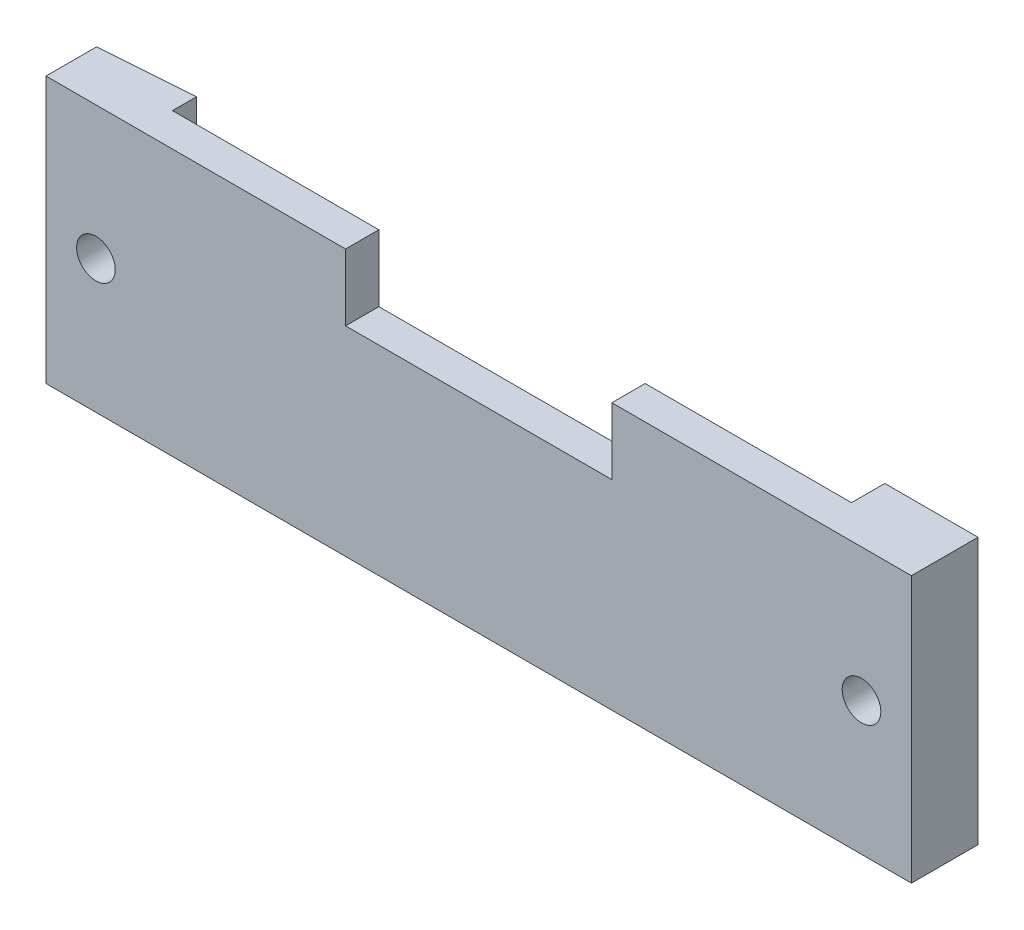
SolidWorks part; units mm, degrees
ref_plane "Front Plane" through (0, 0, 0) normal (0, 0, 1) x (1, 0, 0)
ref_plane "Top Plane" through (0, 0, 0) normal (0, 1, 0) x (1, 0, 0)
ref_plane "Right Plane" through (0, 0, 0) normal (1, 0, 0) x (0, 0, -1)
sketch "Sketch1" plane through (0, 0, 0) normal (0, 0, 1) x (1, 0, 0)
  line L0 (0, 0) -> (32.5, 0)
  line L1 (0, 0) -> (-32.5, 0)
  line L2 (-32.5, 0) -> (-32.5, 20)
  line L3 (32.5, 0) -> (32.5, 20)
  line L4 (32.5, 20) -> (-32.5, 20)
  dimension "D1" = 32.5
  dimension "D2" = 32.5
  dimension "D3" = 20
extrude "Boss-Extrude1" add sketch "Sketch1" along normal blind 5
sketch "Sketch2" plane through (0, 0, 0) normal (0, -1, 0) x (1, 0, 0)
  line L0 (-32.5, 0) -> (-25.5, 0) construction
  line L1 (-32.5, 0) -> (32.5, 0) construction
  line L2 (32.5, 0) -> (25.5, 0) construction
  line L3 (-25.5, 0) -> (-25.5, 2.5)
  line L5 (-25.5, 2.5) -> (25.5, 2.5)
  line L6 (25.5, 2.5) -> (25.5, 0)
  line L7 (25.5, 0) -> (-25.5, 0)
  dimension "D1" = 7
  dimension "D2" = 7
  dimension "D3" = 2.5
extrude "Cut-Extrude1" cut sketch "Sketch2" against normal up to next
sketch "Sketch3" plane through (0, 0, 5) normal (0, 0, 1) x (1, 0, 0)
  line L0 (-32.5, 10) -> (-25, 10) construction
  line L1 (-32.5, 20) -> (-32.5, 0) construction
  line L2 (32.5, 10) -> (25, 10) construction
  line L3 (32.5, 0) -> (32.5, 20) construction
  dimension "D1" = 7.5
  dimension "D2" = 7.5
hole_wizard "M3.5x0.6 Tapped Hole4" positions "Sketch10" profile "Sketch11" tap size "M3.5x0.6" standard "BSI" end condition up to next
sketch "Sketch10" plane through (0, 0, 5) normal (0, 0, 1) x (1, 0, 0)
  line L0 (-32.5, 10) -> (-25, 10) construction
  line L1 (32.5, 10) -> (25, 10) construction
  point P0 (-28.75, 10)
  point P4 (28.75, 10)
sketch "Sketch11" plane through (-28.75, 10, 5) normal (1, 0, 0) x (0, -1, 0)
  line L0 (0, 0) -> (0, 5)
  line L1 (0, 5) -> (1.45, 5)
  line L2 (1.45, 5) -> (1.45, 0)
  line L5 (1.45, 0) -> (0, 0)
  line L11 (0, -6.35) -> (0, 107.95) construction
  dimension "Thru Tap Drill Dia." = 2.9
  dimension "Thru Tap Drill Depth" = 5
cosmetic thread "Hole Thread3" parameters "D2"=3.5
cosmetic thread "Hole Thread4" parameters "D2"=3.5
sketch "Sketch12" plane through (0, 0, 5) normal (0, 0, 1) x (1, 0, 0)
  line L0 (0, 20) -> (-10, 20)
  line L1 (32.5, 20) -> (-32.5, 20) construction
  line L2 (0, 20) -> (10, 20)
  line L3 (-10, 20) -> (-10, 15)
  line L4 (-10, 15) -> (10, 15)
  line L5 (10, 15) -> (10, 20)
  dimension "D1" = 10
  dimension "D2" = 10
  dimension "D3" = 5
extrude "Cut-Extrude2" cut sketch "Sketch12" against normal up to next
sketch "Sketch13" plane through (0, 0, 0) normal (0, -1, 0) x (1, 0, 0)
  line L0 (25.5, 0) -> (25.5, 0.7)
  line L1 (25.5, 0) -> (25.5, 2.5) construction
  line L2 (32.5, 0) -> (32.5, 1.2)
  line L3 (32.5, 5) -> (32.5, 0) construction
  line L4 (25.5, 0) -> (32.5, 0)
  line L5 (25.5, 0.7) -> (32.5, 1.2)
  dimension "D1" = 0.7
  dimension "D2" = 1.2
sketch "Sketch14" plane through (0, 0, 0) normal (0, -1, 0) x (1, 0, 0)
  line L0 (-25.5, 0) -> (-25.5, 0.7)
  line L2 (-25.5, 2.5) -> (-25.5, 0) construction
  line L3 (-32.5, 0) -> (-32.5, 1.2)
  line L4 (-32.5, 5) -> (-32.5, 0) construction
  line L5 (-32.5, 0) -> (-25.5, 0)
  line L6 (-32.5, 1.2) -> (-25.5, 0.7)
  dimension "D1" = 0.7
  dimension "D2" = 1.2
extrude "Cut-Extrude4" cut sketch "Sketch14" against normal up to next
